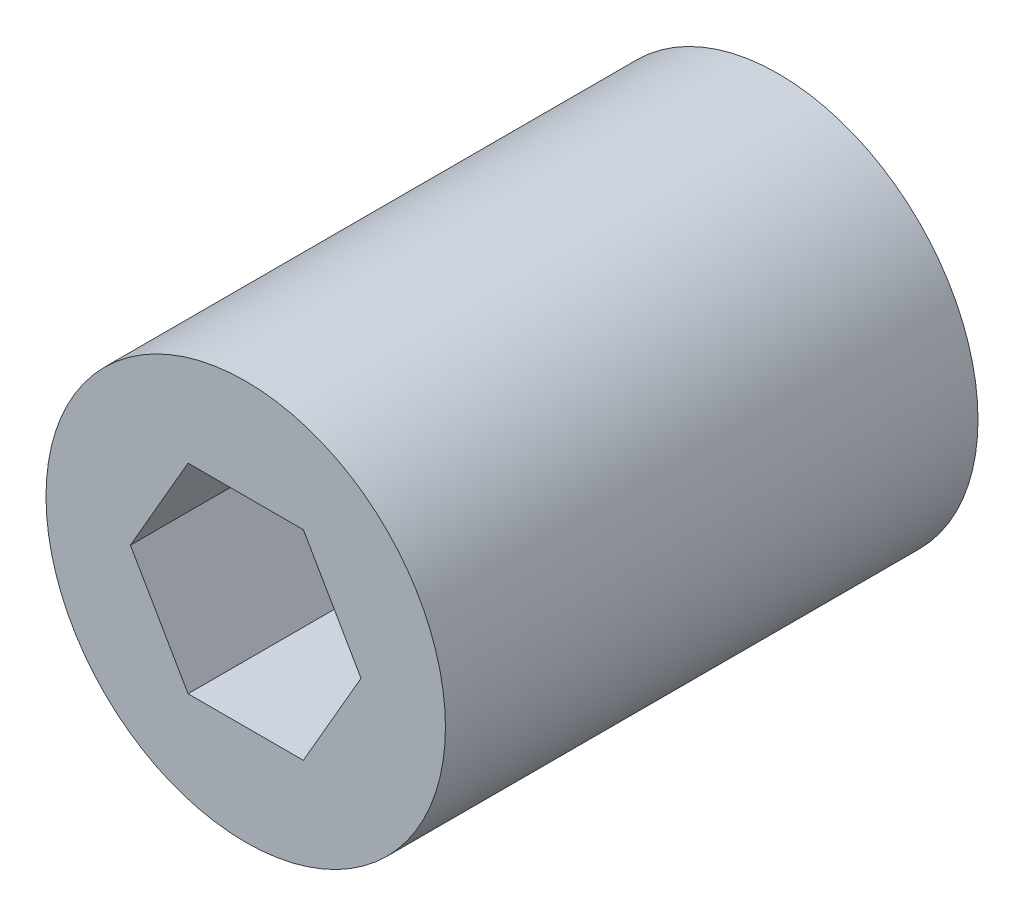
SolidWorks part; units mm, degrees
ref_plane "Front Plane" through (0, 0, 0) normal (0, 0, 1) x (1, 0, 0)
ref_plane "Top Plane" through (0, 0, 0) normal (0, 1, 0) x (1, 0, 0)
ref_plane "Right Plane" through (0, 0, 0) normal (1, 0, 0) x (0, 0, -1)
sketch "S01 - M3 headless body" plane through (0, 0, 0) normal (0, 0, 1) x (1, 0, 0)
  circle A0 centre (0, 0) radius 1.5
  dimension "D1" = 3
extrude "01 - M3 headless body" add sketch "S01 - M3 headless body" along normal blind 4
sketch "S02 - 1.5 mm hex socket" plane through (0, 0, 0) normal (0, 0, 1) x (1, 0, 0)
  line L0 (0.866, 0) -> (0.433, 0.75)
  line L1 (0.433, 0.75) -> (-0.433, 0.75)
  line L2 (-0.433, 0.75) -> (-0.866, 0)
  line L3 (-0.866, 0) -> (-0.433, -0.75)
  line L4 (-0.433, -0.75) -> (0.433, -0.75)
  line L5 (0.433, -0.75) -> (0.866, 0)
  dimension "D1" = 0.433
  dimension "D2" = 0.866
  dimension "D3" = 0.433
  dimension "D4" = 0.866
  dimension "D5" = 0.75
  dimension "D6" = 0.75
extrude "02 - 1.5 mm hex socket" cut sketch "S02 - 1.5 mm hex socket" along normal blind 1.3 from offset 2.8
